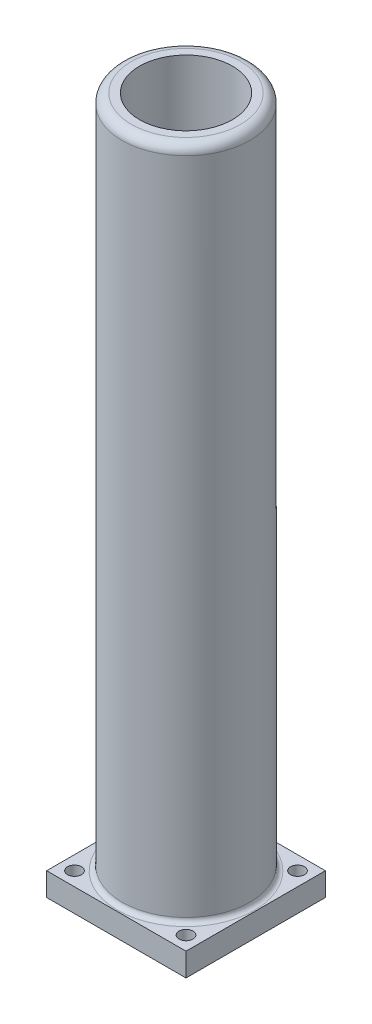
SolidWorks part; units mm, degrees
material "3.0255 (EN-AW 1350A)"
ref_plane "Płaszczyzna przednia" through (0, 0, 0) normal (0, 0, 1) x (1, 0, 0)
ref_plane "Płaszczyzna górna" through (0, 0, 0) normal (0, 1, 0) x (1, 0, 0)
ref_plane "Płaszczyzna prawa" through (0, 0, 0) normal (1, 0, 0) x (0, 0, -1)
sketch "Szkic1" plane through (0, 0, 0) normal (0, 1, 0) x (1, 0, 0)
  line L1 (-30, -30) -> (30, -30)
  line L2 (-30, -30) -> (-30, 30)
  line L3 (-30, 30) -> (30, 30)
  line L4 (30, -30) -> (30, 30)
  line L5 (-30, -30) -> (30, 30) construction
  line L6 (-30, 30) -> (30, -30) construction
  point P0 (0, 0)
  dimension "D1" = 60
  dimension "D2" = 60
extrude "Dodanie-wyciągnięcie1" add sketch "Szkic1" along normal blind 300
sketch "Szkic2" plane through (0, 300, 0) normal (0, 1, 0) x (1, 0, 0)
  circle A0 centre (0, 0) radius 27.5
  point P0 (0, 0)
  dimension "D1" = 55
extrude "Wytnij-wyciągnięcie1" cut sketch "Szkic2" against normal blind 290 flip side to cut
sketch "Szkic3" plane through (0, 10, 0) normal (0, 1, 0) x (1, 0, 0)
  line L0 (-30, 30) -> (-30, -30) construction
  line L2 (-30, -30) -> (30, -30) construction
  line L3 (0, -33) -> (0, 33) construction
  line L4 (-33, 0) -> (33, 0) construction
  circle A0 centre (-24, -24) radius 3
  circle A1 centre (24, -24) radius 3
  circle A2 centre (24, 24) radius 3
  circle A3 centre (-24, 24) radius 3
  dimension "D1" = 6
  dimension "D2" = 6
  dimension "D3" = 6
sketch "Szkic5" plane through (0, 300, 0) normal (0, 1, 0) x (1, 0, 0)
  circle A0 centre (0, 0) radius 20
  dimension "D1" = 40
extrude "Wytnij-wyciągnięcie3" cut sketch "Szkic5" against normal through all
fillet "Zaokrąglenie2" radius 2 1 edges at (0, 10, 27.5)
fillet "Zaokrąglenie3" radius 4 1 edges at (0, 300, 27.5)
hole_wizard "Otwory ustalające Ø6.0mm1" positions "Szkic6" profile "Szkic7" hole size "Ø6.0" standard "ISO" end condition through all
sketch "Szkic6" plane through (0, 10, 0) normal (0, 1, 0) x (1, 0, 0)
  point P0 (-24, -24)
  point P3 (-24, 24)
  point P6 (24, 24)
  point P9 (24, -24)
sketch "Szkic7" plane through (-24, 10, 24) normal (1, 0, 0) x (0, 0, 1)
  line L0 (0, 0) -> (0, 10)
  line L1 (0, 10) -> (3, 10)
  line L2 (3, 10) -> (3, 0)
  line L5 (3, 0) -> (0, 0)
  line L11 (0, -6.35) -> (0, 107.95) construction
  dimension "Średnica otworu na wylot" = 6
  dimension "Głębokość otworu na wylot" = 10
